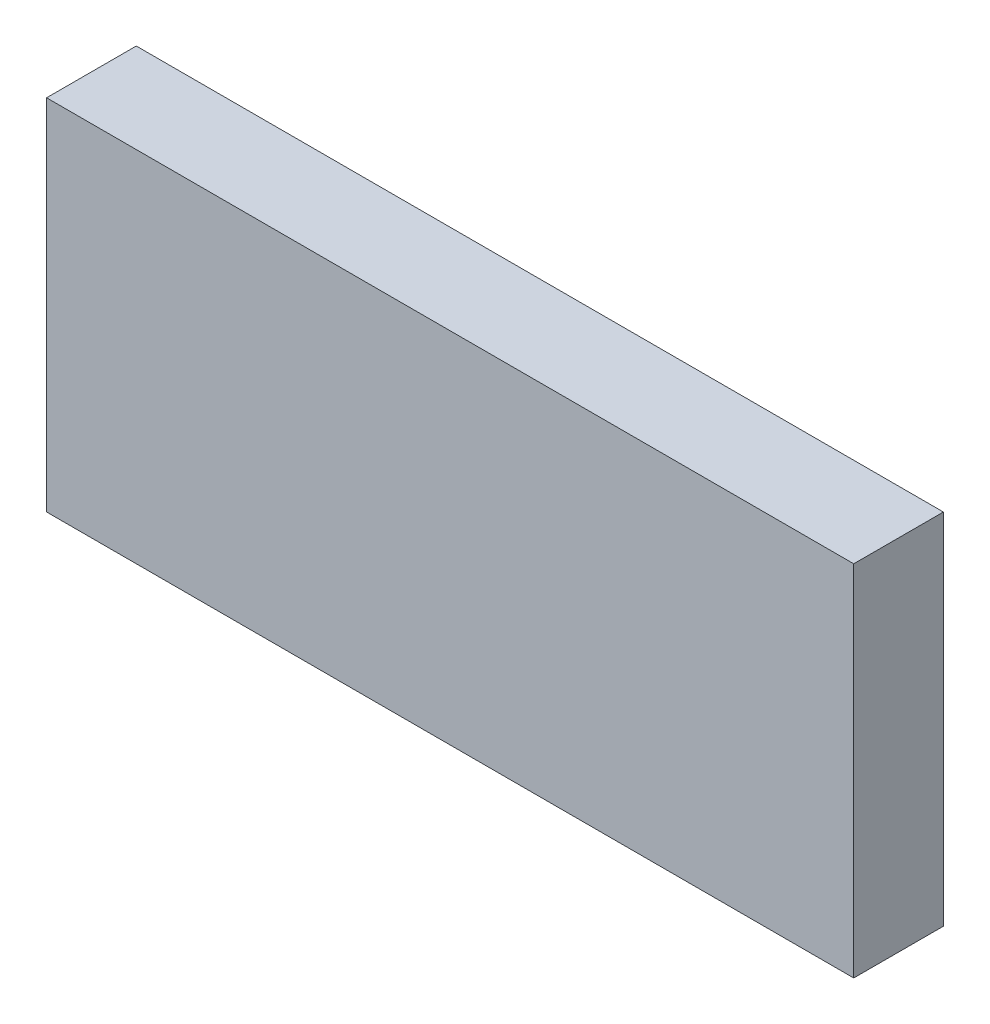
SolidWorks part; units mm, degrees
ref_plane "Front Plane" through (0, 0, 0) normal (0, 0, 1) x (1, 0, 0)
ref_plane "Top Plane" through (0, 0, 0) normal (0, 1, 0) x (1, 0, 0)
ref_plane "Right Plane" through (0, 0, 0) normal (1, 0, 0) x (0, 0, -1)
sketch "Sketch1" plane through (0, 0, 0) normal (0, 0, 1) x (1, 0, 0)
  line L1 (-42.8625, 19.05) -> (42.8625, 19.05)
  line L2 (-42.8625, 19.05) -> (-42.8625, -19.05)
  line L3 (-42.8625, -19.05) -> (42.8625, -19.05)
  line L4 (42.8625, 19.05) -> (42.8625, -19.05)
  line L5 (-42.8625, 19.05) -> (42.8625, -19.05) construction
  line L6 (-42.8625, -19.05) -> (42.8625, 19.05) construction
  point P0 (0, 0)
  dimension "D1" = 85.725
  dimension "D2" = 38.1
extrude "Boss-Extrude1" add sketch "Sketch1" along normal blind 9.525
